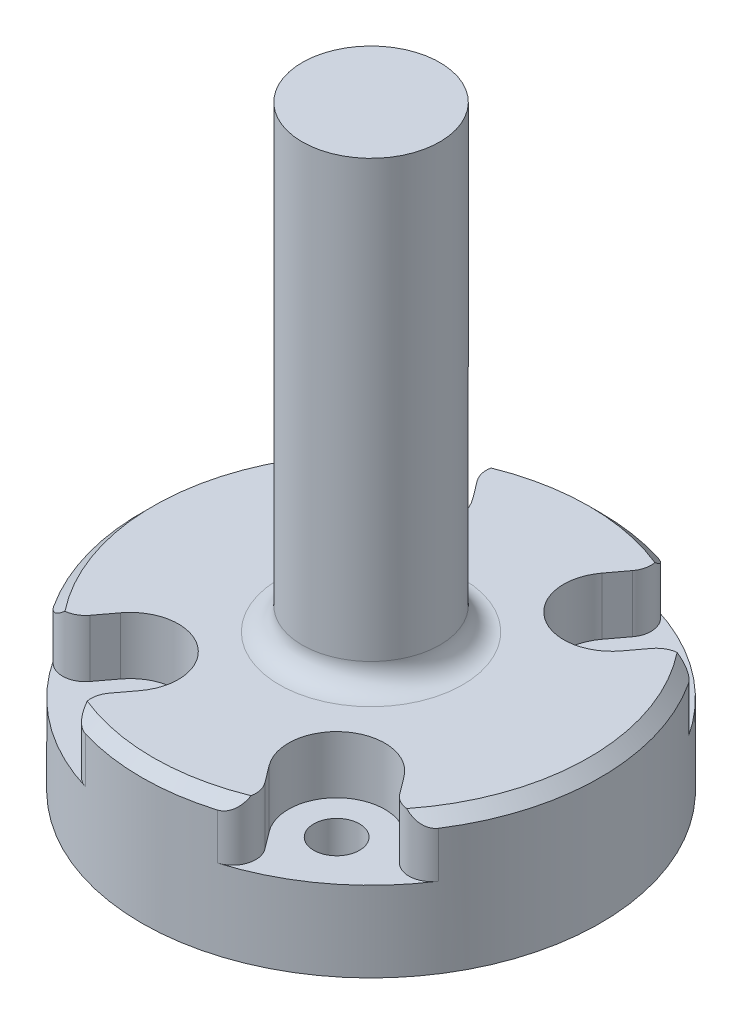
SolidWorks part; units mm, degrees
ref_plane "前视基准面" through (0, 0, 0) normal (0, 0, 1) x (1, 0, 0)
ref_plane "上视基准面" through (0, 0, 0) normal (0, 1, 0) x (1, 0, 0)
ref_plane "右视基准面" through (0, 0, 0) normal (1, 0, 0) x (0, 0, -1)
other "Configuration Table"
sketch "草图1" plane through (0, 0, 0) normal (0, 0, 1) x (1, 0, 0)
  line L0 (0, 9.9473) -> (0, -12.0981) construction
  line L1 (0, 26) -> (3, 26)
  line L2 (3, 26) -> (3, 6)
  line L3 (3, 6) -> (9.5, 6)
  line L4 (10, 5.5) -> (10, 0)
  line L5 (10, 0) -> (5, 0)
  line L6 (5, 0) -> (5, 3)
  line L7 (5, 3) -> (0, 3)
  line L8 (9.5, 6) -> (10, 5.5)
  line L9 (0, 26) -> (0, 3)
  line L10 (6, 7.6882) -> (6, -3.7802) construction
  point P7 (10, 6)
  dimension "D1" = 6
  dimension "D2" = 10
  dimension "D3" = 10
  dimension "D4" = 20
  dimension "D5" = 3
  dimension "D6" = 3
  dimension "D7" = 6
revolve "旋转1" add sketch "草图1" angle 360 about L0
sketch "草图2" plane through (0, 6, 0) normal (0, 1, 0) x (1, 0, 0)
  line L1 (4.5, -6) -> (-4.5, -6) construction
  line L2 (4.5, -6) -> (4.5, 6) construction
  line L3 (4.5, 6) -> (-4.5, 6) construction
  line L4 (-4.5, -6) -> (-4.5, 6) construction
  line L5 (4.5, -6) -> (-4.5, 6) construction
  line L6 (4.5, 6) -> (-4.5, -6) construction
  circle A0 centre (-4.5, 6) radius 1
  circle A1 centre (4.5, 6) radius 1
  circle A2 centre (4.5, -6) radius 1
  circle A3 centre (-4.5, -6) radius 1
  point P0 (4.6354, -6)
  point P2 (0, 0)
  point P16 (-4.3603, 6)
  dimension "D1" = 9
  dimension "D2" = 2
  dimension "D4" = 12
extrude "切除-拉伸1" cut sketch "草图2" against normal blind 10
sketch "草图3" plane through (0, 6, 0) normal (0, 1, 0) x (1, 0, 0)
  line L0 (0, 0) -> (-4.5, -6)
  line L1 (-6.18, -4.74) -> (-9.1576, -8.7101)
  line L2 (-9.1576, -8.7101) -> (-5.7976, -11.2301)
  line L3 (-5.7976, -11.2301) -> (-2.82, -7.26)
  line L4 (0, -55) -> (0, 55) construction
  line L5 (5.7976, -11.2301) -> (2.82, -7.26)
  line L6 (9.1576, -8.7101) -> (5.7976, -11.2301)
  line L7 (6.18, -4.74) -> (9.1576, -8.7101)
  line L8 (-55, 0) -> (55, 0) construction
  line L9 (6.18, 4.74) -> (9.1576, 8.7101)
  line L10 (9.1576, 8.7101) -> (5.7976, 11.2301)
  line L11 (5.7976, 11.2301) -> (2.82, 7.26)
  line L12 (-5.7976, 11.2301) -> (-2.82, 7.26)
  line L13 (-9.1576, 8.7101) -> (-5.7976, 11.2301)
  line L14 (-6.18, 4.74) -> (-9.1576, 8.7101)
  arc A3 (-2.82, -7.26) -> (-6.18, -4.74) centre (-4.5, -6) ccw
  arc A4 (2.82, -7.26) -> (6.18, -4.74) centre (4.5, -6) cw
  arc A5 (2.82, 7.26) -> (6.18, 4.74) centre (4.5, 6) ccw
  arc A6 (-2.82, 7.26) -> (-6.18, 4.74) centre (-4.5, 6) cw
  point P11 (-5.7976, -11.2301)
  point P15 (-2.82, -7.2803)
  point P18 (-3.4217, -7.802)
  dimension "D3" = 4.2
  dimension "D5" = 2.1
extrude "切除-拉伸2" cut sketch "草图3" against normal blind 2.5
fillet "圆角1" radius 1 8 edges at (7.5462, 4.5, -6.5616) (4.1862, 4.5, -9.0816) (4.1862, 4.5, 9.0816) (7.5462, 4.5, 6.5616) (-4.1862, 4.5, 9.0816) (-7.5462, 4.5, 6.5616) (-7.5462, 4.5, -6.5616) (-4.1862, 4.5, -9.0816)
fillet "圆角2" radius 1 1 edges at (0, 6, 3)
